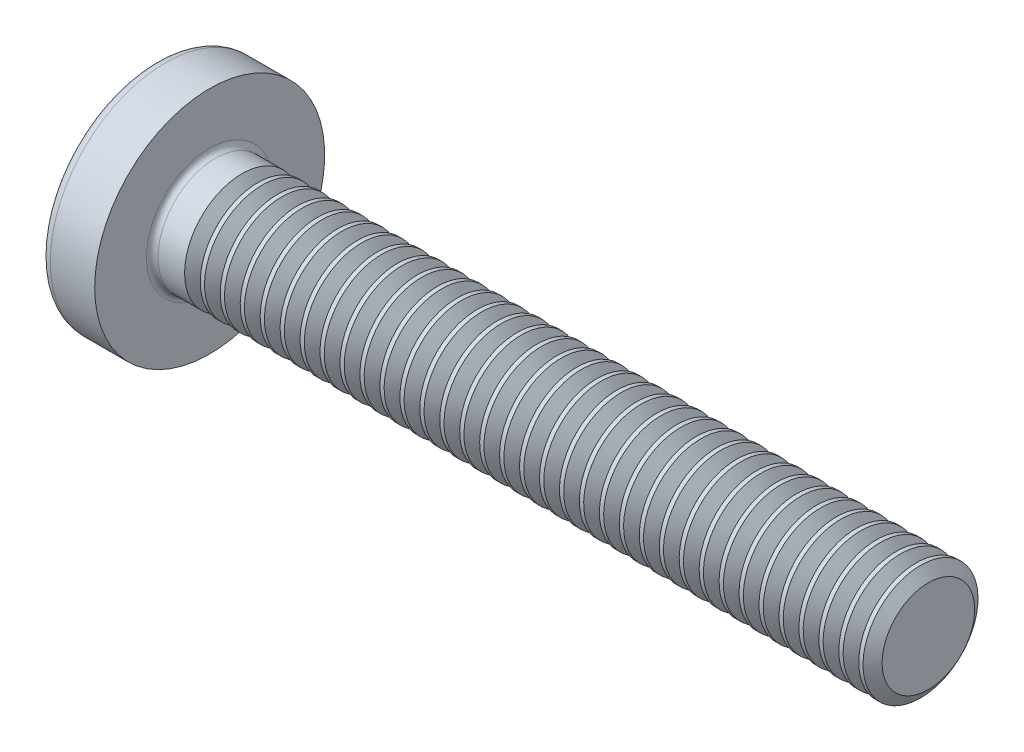
SolidWorks part; units mm, degrees
ref_plane "Plane1" through (0, 0, 0) normal (0, 0, 1) x (1, 0, 0)
ref_plane "Plane2" through (0, 0, 0) normal (0, 1, 0) x (1, 0, 0)
ref_plane "Plane3" through (0, 0, 0) normal (1, 0, 0) x (0, 0, -1)
sketch "BodySke" plane through (0, 0, 0) normal (0, 0, 1) x (1, 0, 0)
  line L0 (3.1, 2) -> (3.1, 4)
  line L1 (3.45, 6.35) -> (3.45, -3.175) construction
  line L2 (-25.4, 0) -> (127, 0) construction
  line L3 (28.1, 0) -> (0, 0)
  line L4 (3.1, 2) -> (28.1, 2)
  line L5 (28.1, 2) -> (28.1, 0)
  line L6 (1.5553, 4) -> (3.1, 4)
  line L8 (3.1, 6.35) -> (3.1, -3.175) construction
  arc A0 (1.2654, 3.8534) -> (0, 0) centre (6.5, 0) ccw
  arc A2 (1.2654, 3.8534) -> (1.5553, 4) centre (1.5553, 3.64) cw
  dimension "Head_crown_rad" = 6.5
  dimension "Head_fillet_rad" = 0.36
  dimension "Length" = 25
  dimension "Head_ht" = 3.1
  dimension "Head_dia" = 8
  dimension "Advance" = 0.7
  dimension "Thread_nom" = 25
  dimension "Diameter" = 4
revolve "Base-Revolve" add sketch "BodySke"
cosmetic thread "ThreadCosmetic" [suppressed]
fillet "Fillet1" radius 0.2 1 edges at (3.1, 0, 2)
sketch "Sketch3" plane through (0, 0, 0) normal (1, 0, 0) x (0, 0, -1)
  line L0 (0.515, -2.15) -> (-0.515, -2.15)
  line L1 (0.515, -2.15) -> (0.515, 2.15)
  line L2 (-0.515, 2.15) -> (0.515, 2.15)
  line L3 (-0.515, 2.15) -> (-0.515, -2.15)
  dimension "Cross_dia" = 4.3
  dimension "D1" = 2.15
  dimension "Cross_width" = 1.03
  dimension "D2" = 0.515
ref_plane "Plane4" through (2.34, 0, 0) normal (1, 0, 0) x (0, 0, -1)
sketch "Sketch4" plane through (2.34, 0, 0) normal (1, 0, 0) x (0, 0, -1)
  line L0 (0.515, -0.9833) -> (-0.515, -0.9833)
  line L1 (0.515, -0.9833) -> (0.515, 0.9833)
  line L2 (-0.515, 0.9833) -> (0.515, 0.9833)
  line L3 (-0.515, 0.9833) -> (-0.515, -0.9833)
  dimension "D1" = 1.03
  dimension "D2" = 1.9666
  dimension "D3" = 0.515
  dimension "D4" = 0.9833
loft "Recess" cut profiles "Sketch3", "Sketch4"
pattern_circular "RecPat" count 2 every 90 about axis through (0, 0, 0) along (1, 0, 0) of "Recess"
sketch "RecCorSke" plane through (0, 0, 0) normal (0, 0, 1) x (1, 0, 0)
  line L0 (-3.175, 0) -> (15.875, 0) construction
  line L1 (-25.4, 0) -> (127, 0) construction
  line L2 (0, 0) -> (0, 1.0146)
  line L3 (0, 1.0146) -> (2.34, 0.851)
  line L4 (2.34, 0.851) -> (2.6165, 0)
  line L5 (2.6165, 0) -> (0, 0)
  dimension "Diameter" = 1.702
  dimension "Depth" = 2.34
  dimension "Draft_angle" = 4
  dimension "Bottom_angle" = 18
revolve "RecessCore" cut sketch "RecCorSke" angle 360 about L0
sketch "ThdSchSke" plane through (0, 0, 0) normal (0, 0, 1) x (1, 0, 0)
  line L0 (4.5, -1.61) -> (4.2269, -2)
  line L1 (4.5, -1.61) -> (4.7731, -2)
  line L2 (4.7731, -2) -> (4.7731, -2.5)
  line L3 (-3.175, 0) -> (5.1513, 0) construction
  line L5 (4.7731, -2.5) -> (4.2269, -2.5)
  line L6 (4.2269, -2.5) -> (4.2269, -2)
  dimension "Diameter" = 4
  dimension "SideAngle" = 55
  dimension "VeeAngle" = 70
  dimension "Thread_minor" = 3.22
  dimension "Overcut" = 5
  dimension "Start" = 4.5
revolve "ThreadSchematic" cut sketch "ThdSchSke" angle 360 about L3
pattern_linear "ThdSchPat" count 35 spacing 0.6941 along (1, 0, 0) of "ThreadSchematic"
equation "\"D1@Sketch3\" = \"Cross_dia@Sketch3\" / 2"
equation "\"D2@Sketch3\" = \"Cross_width@Sketch3\" / 2"
equation "\"Depth@RecCorSke\" = \"Cross_depth@Plane4\""
equation "\"D1@Sketch4\" = \"Cross_width@Sketch3\""
equation "\"D2@Sketch4\" = \"Cross_dia@Sketch3\" - 2.0 * \"Cross_depth@Plane4\" * tan(26.5  * 0.017453292)"
equation "\"D3@Sketch4\" = \"D1@Sketch4\" / 2"
equation "\"D4@Sketch4\" = \"D2@Sketch4\" / 2"
equation "\"Thread_length@ThreadCosmetic\" = ((sgn( (\"Length@BodySke\" - \"Advance@BodySke\" * 2.0 ) - \"Thread_nom@BodySke\" )-1)*( (\"Length@BodySke\" - \"Advance@BodySke\" * 2.0 ) - \"Thread_nom@BodySke\" ))/-2+ \"Thread_nom@BodySke\""
equation "\"Thread_minor@ThdSchSke\" = \"Thread_minor@ThreadCosmetic\""
equation "\"Diameter@ThdSchSke\" = \"Diameter@BodySke\""
equation "\"Overcut@ThdSchSke\" = \"Diameter@BodySke\" * 1.25"
equation "\"Start@ThdSchSke\" = \"Head_ht@BodySke\" + \"Length@BodySke\" - \"Thread_length@ThreadCosmetic\"  '---Non-countersunk---"
equation "\"Num_threads@ThdSchPat\" = int( \"Thread_length@ThreadCosmetic\" / \"Advance@BodySke\" + 0.999 )  + 1"
equation "\"Advance@ThdSchPat\" = \"Thread_length@ThreadCosmetic\" /  (\"Num_threads@ThdSchPat\" - 1) 'relax it"
